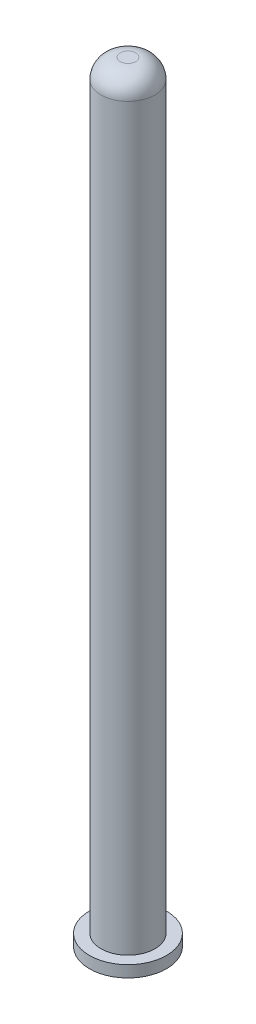
SolidWorks part; units mm, degrees
ref_plane "Front Plane" through (0, 0, 0) normal (0, 0, 1) x (1, 0, 0)
ref_plane "Top Plane" through (0, 0, 0) normal (0, 1, 0) x (1, 0, 0)
ref_plane "Right Plane" through (0, 0, 0) normal (1, 0, 0) x (0, 0, -1)
sketch "Sketch1" plane through (0, 0, 0) normal (1, 0, 0) x (0, 0, -1)
  line L0 (0, 200) -> (0, 0)
  line L1 (0, 0) -> (10, 0)
  line L2 (10, 0) -> (10, 3)
  line L3 (10, 3) -> (7, 3)
  line L4 (7, 3) -> (7, 200)
  line L5 (7, 200) -> (0, 200)
  dimension "D1" = 200
  dimension "D2" = 7
  dimension "D3" = 10
  dimension "D4" = 3
revolve "Revolve1" add sketch "Sketch1" angle 360 about L0
fillet "Fillet1" radius 5 1 edges at (0, 200, 7)
